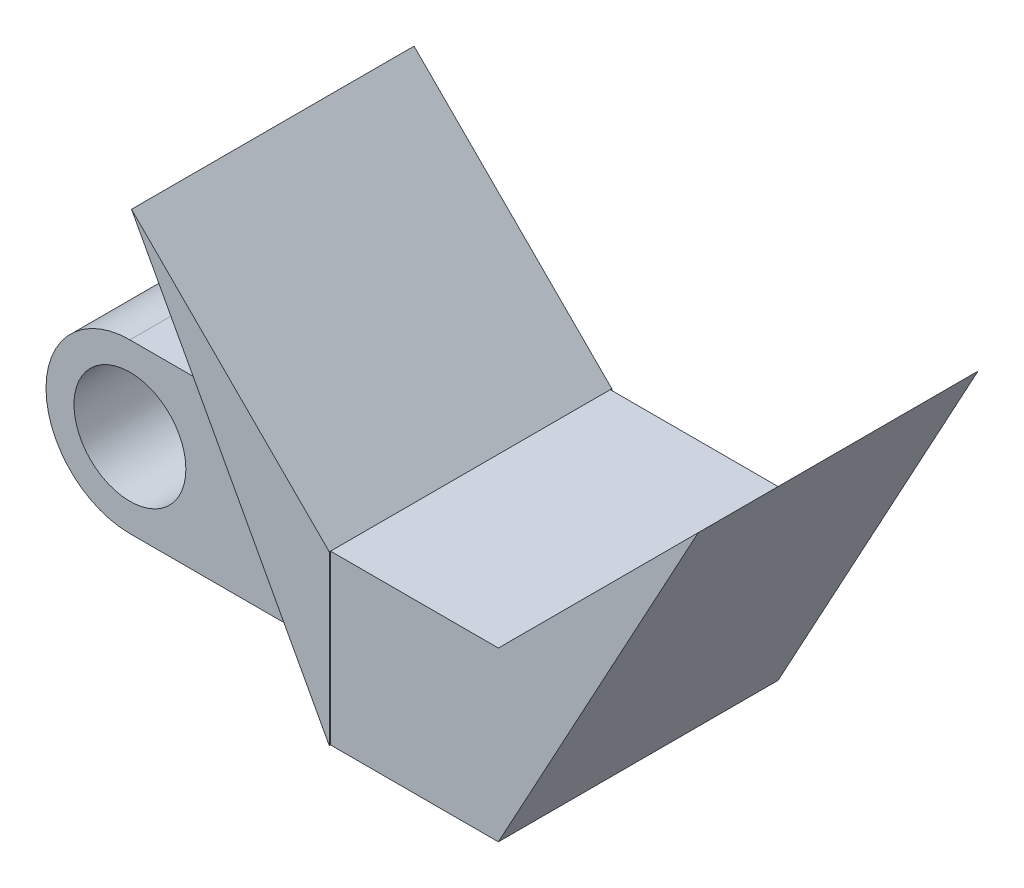
SolidWorks part; units mm, degrees
ref_plane "Alzado" through (0, 0, 0) normal (0, 0, 1) x (1, 0, 0)
ref_plane "Planta" through (0, 0, 0) normal (0, 1, 0) x (1, 0, 0)
ref_plane "Vista lateral" through (0, 0, 0) normal (1, 0, 0) x (0, 0, -1)
sketch "Croquis1" plane through (0, 0, 0) normal (0, 0, 1) x (1, 0, 0)
  line L0 (0, 0) -> (30, 0) construction
  line L2 (0, 7.5) -> (30, 7.5)
  line L3 (0, -7.5) -> (30, -7.5)
  line L4 (30, 7.5) -> (37.5, 7.5)
  line L6 (30, -7.5) -> (37.5, -7.5)
  line L7 (37.5, 7.5) -> (37.5, -7.5)
  arc A7 (0, 7.5) -> (0, -7.5) centre (0, 0) ccw
  circle A8 centre (0, 0) radius 5
  point P5 (15, 0)
extrude "Saliente-Extruir1" add sketch "Croquis1" along normal blind 10
sketch "Croquis4" plane through (0, -7.5, 0) normal (0, -1, 0) x (1, 0, 0)
  line L1 (25.3191, 17.39) -> (40.3191, 17.39)
  line L2 (25.3191, 17.39) -> (25.3191, -7.61)
  line L3 (25.3191, -7.61) -> (40.3191, -7.61)
  line L4 (40.3191, 17.39) -> (40.3191, -7.61)
  line L5 (0, 0) -> (37.5, 0) construction
  dimension "D1" = 7.61
extrude "Saliente-Extruir3" add sketch "Croquis4" against normal blind 15
sketch "Croquis11" plane through (0, 0, -7.61) normal (0, 0, -1) x (-1, 0, 0)
  line L0 (-40.3191, 7.5) -> (-58.185, 25.3659)
  line L1 (-58.185, 25.3659) -> (-40.3191, -7.5)
  line L2 (-40.3191, 7.5) -> (-40.3191, -7.5)
extrude "Saliente-Extruir9" add sketch "Croquis11" against normal blind 25
sketch "Croquis14" plane through (0, 0, 0) normal (0, 0, -1) x (-1, 0, 0)
  line L0 (-25.3191, 7.5) -> (-7.6415, 25.1777)
  line L1 (-7.6415, 25.1777) -> (-25.3191, -7.5)
  line L2 (-25.3191, 7.5) -> (-25.3191, -7.5)
extrude "Saliente-Extruir10" add sketch "Croquis14" against normal blind 17.5 and the other way blind 7.75
scale "Escala1" bodies to scale 111 scale about centroid uniform scaling yes scale factor 0.75
